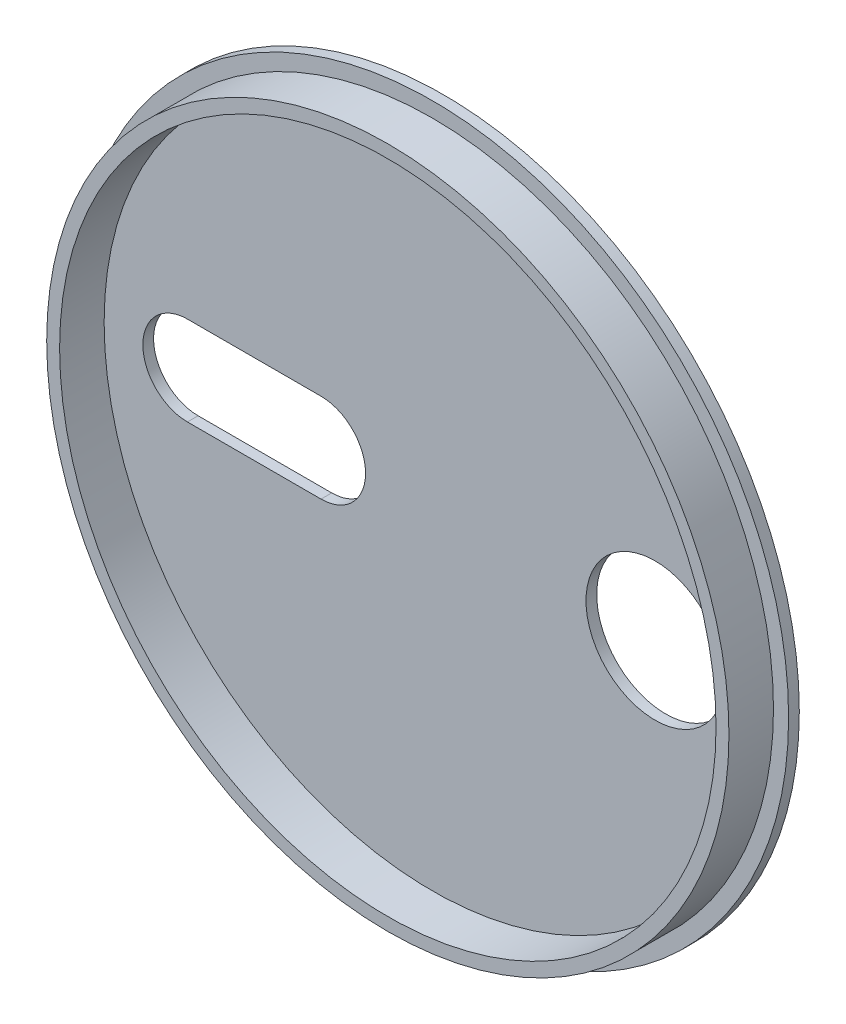
SolidWorks part; units mm, degrees
material "PET"
ref_plane "Ebene vorne" through (0, 0, 0) normal (0, 0, 1) x (1, 0, 0)
ref_plane "Ebene oben" through (0, 0, 0) normal (0, 1, 0) x (1, 0, 0)
ref_plane "Ebene rechts" through (0, 0, 0) normal (1, 0, 0) x (0, 0, -1)
sketch "Sketch1" plane through (0, 0, 0) normal (0, 0, 1) x (1, 0, 0)
  circle A0 centre (0, 0) radius 40
  dimension "D1" = 80
extrude "Boss-Extrude1" add sketch "Sketch1" along normal blind 1.2
sketch "Sketch2" plane through (0, 0, 1.2) normal (0, 0, 1) x (1, 0, 0)
  line L0 (40, 0) -> (25, 0)
  circle A0 centre (0, 0) radius 40 construction
  circle A1 centre (25, 0) radius 7.75
  dimension "D2" = 15.5
  dimension "D1" = 15
extrude "Cut-Extrude1" cut sketch "Sketch2" against normal up to next
sketch "Sketch3" plane through (0, 0, 1.2) normal (0, 0, 1) x (1, 0, 0)
  line L0 (0, 0) -> (-40, 0) construction
  line L1 (-40, 0) -> (-27.5, 0)
  line L2 (0, 0) -> (-12.5, 0)
  line L3 (-27.5, 0) -> (-12.5, 0) construction
  line L4 (-27.5, 5) -> (-12.5, 5)
  line L5 (-27.5, -5) -> (-12.5, -5)
  circle A0 centre (0, 0) radius 40 construction
  arc A1 (-27.5, 5) -> (-27.5, -5) centre (-27.5, 0) ccw
  arc A2 (-12.5, -5) -> (-12.5, 5) centre (-12.5, 0) ccw
  point P6 (-20, 0)
  dimension "D3" = 5
  dimension "D1" = 12.5
  dimension "D2" = 12.5
extrude "Cut-Extrude2" cut sketch "Sketch3" against normal up to next
sketch "Sketch4" plane through (0, 0, 1.2) normal (0, 0, 1) x (1, 0, 0)
  circle A0 centre (0, 0) radius 38.3
  dimension "D1" = 76.6
extrude "Boss-Extrude2" add sketch "Sketch4" along normal blind 5
sketch "Sketch5" plane through (0, 0, 6.2) normal (0, 0, 1) x (1, 0, 0)
  circle A0 centre (0, 0) radius 36.85
  dimension "D1" = 73.7
extrude "Cut-Extrude3" cut sketch "Sketch5" against normal blind 5
